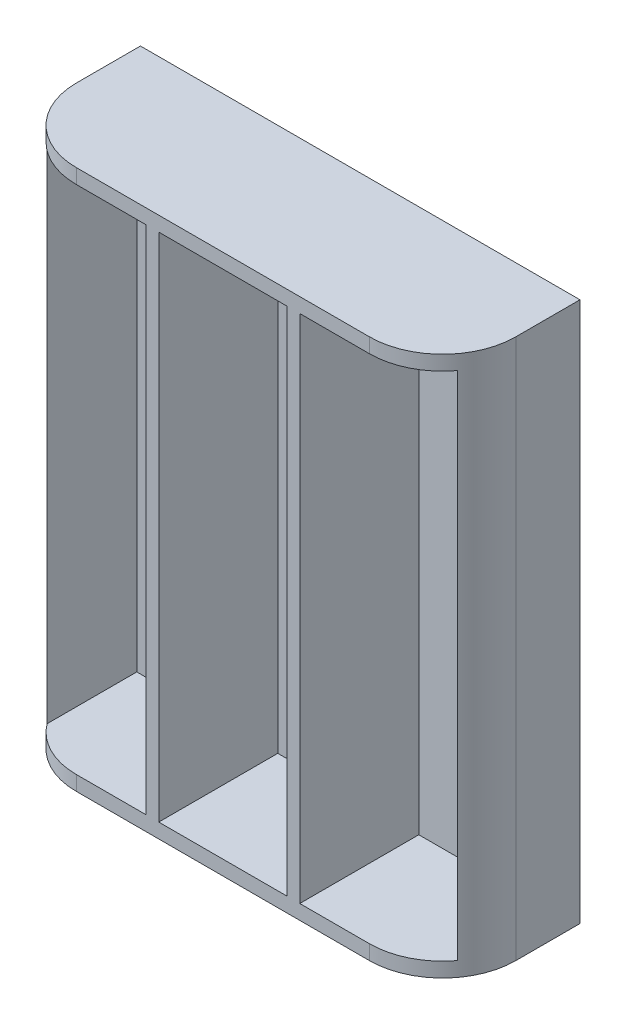
SolidWorks part; units mm, degrees
ref_plane "Front" through (0, 0, 0) normal (0, 0, 1) x (1, 0, 0)
ref_plane "Top" through (0, 0, 0) normal (0, 1, 0) x (1, 0, 0)
ref_plane "Right" through (0, 0, 0) normal (1, 0, 0) x (0, 0, -1)
sketch "Sketch1" plane through (0, 0, 0) normal (0, 0, 1) x (1, 0, 0)
  line L1 (-24, -29.5) -> (24, -29.5)
  line L2 (-24, -29.5) -> (-24, 29.5)
  line L3 (-24, 29.5) -> (24, 29.5)
  line L4 (24, -29.5) -> (24, 29.5)
  line L5 (-24, -29.5) -> (24, 29.5) construction
  line L6 (-24, 29.5) -> (24, -29.5) construction
  point P0 (0, 0)
  dimension "D1" = 59
  dimension "D2" = 48
extrude "Boss-Extrude1" add sketch "Sketch1" along normal blind 2
sketch "Sketch2" plane through (0, -29.5, 0) normal (0, -1, 0) x (1, 0, 0)
  line L0 (-16, 15) -> (16, 15)
  line L1 (0, 0) -> (0, 15) construction
  line L2 (-24, 0) -> (24, 0) construction
  line L3 (-24, 2) -> (-24, 7)
  line L4 (-24, 2) -> (24, 2)
  line L5 (-24, 2) -> (24, 2) construction
  line L6 (24, 2) -> (24, 7)
  arc A0 (-24, 7) -> (-16, 15) centre (-16, 7) cw
  arc A1 (24, 7) -> (16, 15) centre (16, 7) ccw
  point P17 (0, 2)
  dimension "D1" = 15
  dimension "D2" = 7
extrude "Boss-Extrude2" add sketch "Sketch2" against normal up to surface (59 mm away) up to face at (0, 29.5, 1)
sketch "Sketch3" plane through (0, 0, 15) normal (0, 0, 1) x (1, 0, 0)
  line L0 (-16, 29.5) -> (16, 29.5) construction
  line L1 (-7, 27.9) -> (7, 27.9)
  line L2 (-7, 27.9) -> (-7, -27.9)
  line L3 (-7, -27.9) -> (7, -27.9)
  line L4 (7, 27.9) -> (7, -27.9)
  line L5 (-7, 27.9) -> (7, -27.9) construction
  line L6 (-7, -27.9) -> (7, 27.9) construction
  line L7 (7.7, 29.5) -> (7.7, -29.5) construction
  line L8 (16, -29.5) -> (-16, -29.5) construction
  line L9 (22.4, 27.9) -> (22.4, -27.9)
  line L10 (22.4, -27.9) -> (8.4, -27.9)
  line L11 (8.4, 27.9) -> (8.4, -27.9)
  line L12 (22.4, 27.9) -> (8.4, 27.9)
  line L13 (0, 0) -> (0, -29.5) construction
  line L14 (-8.4, 27.9) -> (-8.4, -27.9)
  line L15 (-22.4, -27.9) -> (-8.4, -27.9)
  line L16 (-22.4, 27.9) -> (-22.4, -27.9)
  line L17 (-22.4, 27.9) -> (-8.4, 27.9)
  point P0 (0, 0)
  dimension "D1" = 14
  dimension "D2" = 1.6
  dimension "D3" = 0.7
extrude "Cut-Extrude1" cut sketch "Sketch3" against normal offset from surface (13 mm away) 2 up to face at (0, 0, 0)
